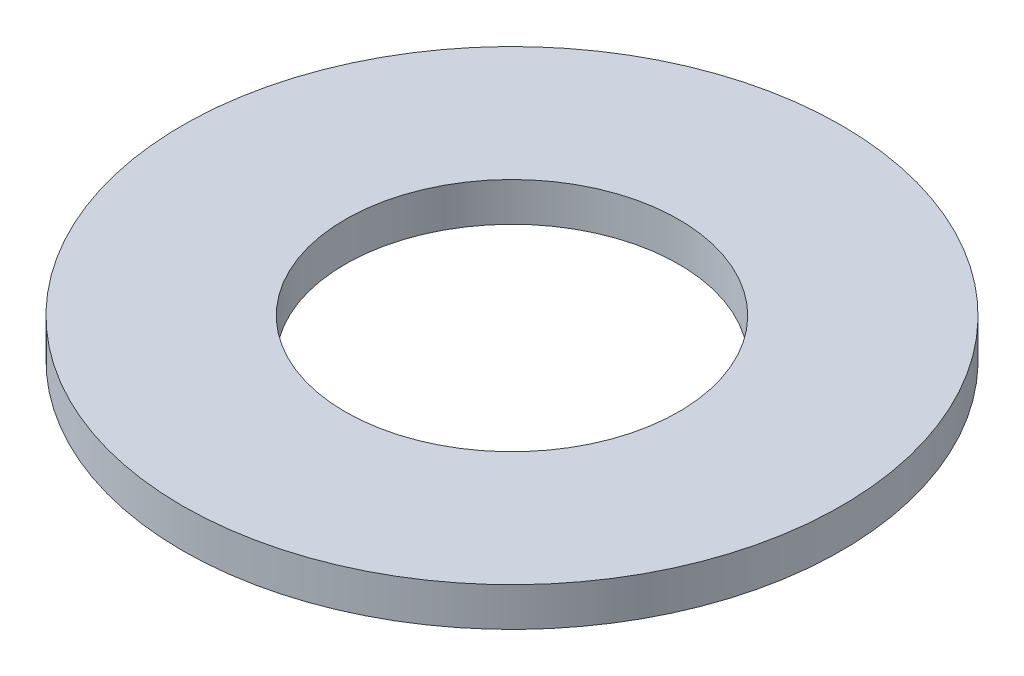
SolidWorks part; units mm, degrees
ref_plane "前视基准面" through (0, 0, 0) normal (0, 0, 1) x (1, 0, 0)
ref_plane "上视基准面" through (0, 0, 0) normal (0, 1, 0) x (1, 0, 0)
ref_plane "右视基准面" through (0, 0, 0) normal (1, 0, 0) x (0, 0, -1)
sketch "草图1" plane through (0, 0, 0) normal (0, 1, 0) x (1, 0, 0)
  circle A0 centre (0, 0) radius 2.15
  circle A1 centre (0, 0) radius 4.25
  dimension "D1" = 4.3
  dimension "D2" = 8.5
extrude "凸台-拉伸1" add sketch "草图1" along normal blind 0.5
